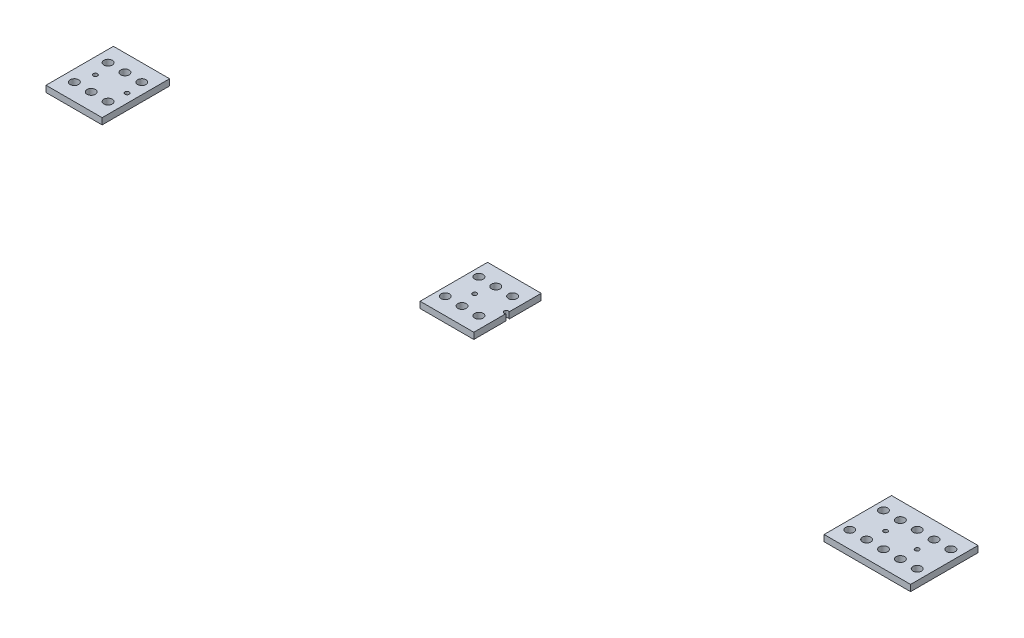
SolidWorks part; units mm, degrees
ref_plane "前基準面" through (0, 0, 0) normal (0, 0, 1) x (1, 0, 0)
ref_plane "上基準面" through (0, 0, 0) normal (0, 1, 0) x (1, 0, 0)
ref_plane "右基準面" through (0, 0, 0) normal (1, 0, 0) x (0, 0, -1)
sketch "草圖1" plane through (0, 0, 0) normal (0, 1, 0) x (1, 0, 0)
  line L1 (437.0323, 21.7005) -> (-14.2241, 21.7005)
  line L2 (437.0323, 21.7005) -> (437.0323, -10.2995)
  line L3 (437.0323, -10.2995) -> (-14.2241, -10.2995)
  line L4 (-14.2241, 21.7005) -> (-14.2241, -10.2995)
  line L5 (211.4041, -10.2995) -> (211.4041, 21.7005) construction
  line L6 (437.0323, 5.7005) -> (-14.2241, 5.7005) construction
  circle A0 centre (-8.7706, 13.7005) radius 2
  circle A1 centre (-8.7706, -2.2995) radius 2
  circle A2 centre (-0.7706, 13.7005) radius 2
  circle A3 centre (-0.7706, -2.2995) radius 2
  circle A4 centre (7.2294, 13.7005) radius 2
  circle A5 centre (7.2294, -2.2995) radius 2
  circle A6 centre (15.2294, 13.7005) radius 2
  circle A7 centre (15.2294, -2.2995) radius 2
  circle A8 centre (23.2294, 13.7005) radius 2
  circle A9 centre (23.2294, -2.2995) radius 2
  circle A10 centre (31.2294, 13.7005) radius 2
  circle A11 centre (31.2294, -2.2995) radius 2
  circle A12 centre (39.2294, 13.7005) radius 2
  circle A13 centre (39.2294, -2.2995) radius 2
  circle A14 centre (47.2294, 13.7005) radius 2
  circle A15 centre (47.2294, -2.2995) radius 2
  circle A16 centre (55.2294, 13.7005) radius 2
  circle A17 centre (55.2294, -2.2995) radius 2
  circle A18 centre (63.2294, 13.7005) radius 2
  circle A19 centre (63.2294, -2.2995) radius 2
  circle A20 centre (71.2294, 13.7005) radius 2
  circle A21 centre (71.2294, -2.2995) radius 2
  circle A22 centre (79.2294, 13.7005) radius 2
  circle A23 centre (79.2294, -2.2995) radius 2
  circle A24 centre (87.2294, 13.7005) radius 2
  circle A25 centre (87.2294, -2.2995) radius 2
  circle A26 centre (95.2294, 13.7005) radius 2
  circle A27 centre (95.2294, -2.2995) radius 2
  circle A28 centre (103.2294, 13.7005) radius 2
  circle A29 centre (103.2294, -2.2995) radius 2
  circle A30 centre (111.2294, 13.7005) radius 2
  circle A31 centre (111.2294, -2.2995) radius 2
  circle A32 centre (119.2294, 13.7005) radius 2
  circle A33 centre (119.2294, -2.2995) radius 2
  circle A34 centre (127.2294, 13.7005) radius 2
  circle A35 centre (127.2294, -2.2995) radius 2
  circle A36 centre (135.2294, 13.7005) radius 2
  circle A37 centre (135.2294, -2.2995) radius 2
  circle A38 centre (143.2294, 13.7005) radius 2
  circle A39 centre (143.2294, -2.2995) radius 2
  circle A40 centre (151.2294, 13.7005) radius 2
  circle A41 centre (151.2294, -2.2995) radius 2
  circle A42 centre (159.2294, 13.7005) radius 2
  circle A43 centre (159.2294, -2.2995) radius 2
  circle A44 centre (167.2294, 13.7005) radius 2
  circle A45 centre (167.2294, -2.2995) radius 2
  circle A46 centre (175.2294, 13.7005) radius 2
  circle A47 centre (175.2294, -2.2995) radius 2
  circle A48 centre (183.2294, 13.7005) radius 2
  circle A49 centre (183.2294, -2.2995) radius 2
  circle A50 centre (191.2294, 13.7005) radius 2
  circle A51 centre (191.2294, -2.2995) radius 2
  circle A52 centre (199.2294, 13.7005) radius 2
  circle A53 centre (199.2294, -2.2995) radius 2
  circle A54 centre (207.2294, 13.7005) radius 2
  circle A55 centre (207.2294, -2.2995) radius 2
  circle A56 centre (215.2294, 13.7005) radius 2
  circle A57 centre (215.2294, -2.2995) radius 2
  circle A58 centre (223.2294, 13.7005) radius 2
  circle A59 centre (223.2294, -2.2995) radius 2
  circle A60 centre (231.2294, 13.7005) radius 2
  circle A61 centre (231.2294, -2.2995) radius 2
  circle A62 centre (239.2294, 13.7005) radius 2
  circle A63 centre (239.2294, -2.2995) radius 2
  circle A64 centre (247.2294, 13.7005) radius 2
  circle A65 centre (247.2294, -2.2995) radius 2
  circle A66 centre (255.2294, 13.7005) radius 2
  circle A67 centre (255.2294, -2.2995) radius 2
  circle A68 centre (263.2294, 13.7005) radius 2
  circle A69 centre (263.2294, -2.2995) radius 2
  circle A70 centre (271.2294, 13.7005) radius 2
  circle A71 centre (271.2294, -2.2995) radius 2
  circle A72 centre (279.2294, 13.7005) radius 2
  circle A73 centre (279.2294, -2.2995) radius 2
  circle A74 centre (287.2294, 13.7005) radius 2
  circle A75 centre (287.2294, -2.2995) radius 2
  circle A76 centre (295.2294, 13.7005) radius 2
  circle A77 centre (295.2294, -2.2995) radius 2
  circle A78 centre (303.2294, 13.7005) radius 2
  circle A79 centre (303.2294, -2.2995) radius 2
  circle A80 centre (311.2294, 13.7005) radius 2
  circle A81 centre (311.2294, -2.2995) radius 2
  circle A82 centre (319.2294, 13.7005) radius 2
  circle A83 centre (319.2294, -2.2995) radius 2
  circle A84 centre (327.2294, 13.7005) radius 2
  circle A85 centre (327.2294, -2.2995) radius 2
  circle A86 centre (335.2294, 13.7005) radius 2
  circle A87 centre (335.2294, -2.2995) radius 2
  circle A88 centre (343.2294, 13.7005) radius 2
  circle A89 centre (343.2294, -2.2995) radius 2
  circle A90 centre (351.2294, 13.7005) radius 2
  circle A91 centre (351.2294, -2.2995) radius 2
  circle A92 centre (359.2294, 13.7005) radius 2
  circle A93 centre (359.2294, -2.2995) radius 2
  circle A94 centre (367.2294, 13.7005) radius 2
  circle A95 centre (367.2294, -2.2995) radius 2
  circle A96 centre (375.2294, 13.7005) radius 2
  circle A97 centre (375.2294, -2.2995) radius 2
  circle A98 centre (383.2294, 13.7005) radius 2
  circle A99 centre (383.2294, -2.2995) radius 2
  circle A100 centre (391.2294, 13.7005) radius 2
  circle A101 centre (391.2294, -2.2995) radius 2
  circle A102 centre (399.2294, 13.7005) radius 2
  circle A103 centre (399.2294, -2.2995) radius 2
  circle A104 centre (407.2294, 13.7005) radius 2
  circle A105 centre (407.2294, -2.2995) radius 2
  circle A106 centre (415.2294, 13.7005) radius 2
  circle A107 centre (415.2294, -2.2995) radius 2
  circle A108 centre (423.2294, 13.7005) radius 2
  circle A109 centre (423.2294, -2.2995) radius 2
  circle A110 centre (431.2294, 13.7005) radius 2
  circle A111 centre (431.2294, -2.2995) radius 2
  circle A112 centre (-6.7706, 5.7005) radius 1
  circle A113 centre (8.2294, 5.7005) radius 1
  circle A114 centre (23.2294, 5.7005) radius 1
  circle A115 centre (38.2294, 5.7005) radius 1
  circle A116 centre (53.2294, 5.7005) radius 1
  circle A117 centre (68.2294, 5.7005) radius 1
  circle A118 centre (83.2294, 5.7005) radius 1
  circle A119 centre (98.2294, 5.7005) radius 1
  circle A120 centre (113.2294, 5.7005) radius 1
  circle A121 centre (128.2294, 5.7005) radius 1
  circle A122 centre (143.2294, 5.7005) radius 1
  circle A123 centre (158.2294, 5.7005) radius 1
  circle A124 centre (173.2294, 5.7005) radius 1
  circle A125 centre (188.2294, 5.7005) radius 1
  circle A126 centre (203.2294, 5.7005) radius 1
  circle A127 centre (218.2294, 5.7005) radius 1
  circle A128 centre (233.2294, 5.7005) radius 1
  circle A129 centre (248.2294, 5.7005) radius 1
  circle A130 centre (263.2294, 5.7005) radius 1
  circle A131 centre (278.2294, 5.7005) radius 1
  circle A132 centre (293.2294, 5.7005) radius 1
  circle A133 centre (308.2294, 5.7005) radius 1
  circle A134 centre (323.2294, 5.7005) radius 1
  circle A135 centre (338.2294, 5.7005) radius 1
  circle A136 centre (353.2294, 5.7005) radius 1
  circle A137 centre (368.2294, 5.7005) radius 1
  circle A138 centre (383.2294, 5.7005) radius 1
  point P1018 (211.4041, 5.7005)
  dimension "D1" = 4
  dimension "D2" = 4
  dimension "D5" = 2
  dimension "D3" = 16
  dimension "D6" = 8
  dimension "D8" = 32
  dimension "D9" = 16
  dimension "D4" = 56
  dimension "D7" = 27
extrude "填料-伸長1" add sketch "草圖1" along normal blind 3
sketch "草圖2" plane through (0, 3, 0) normal (0, 1, 0) x (1, 0, 0)
  line L0 (437.0323, 21.7005) -> (-14.2241, 21.7005) construction
  line L1 (12.4203, 21.7005) -> (163.3256, 21.7005)
  line L2 (12.4203, 21.7005) -> (12.4203, -10.2995)
  line L3 (12.4203, -10.2995) -> (163.3256, -10.2995)
  line L4 (163.3256, 21.7005) -> (163.3256, -10.2995)
  line L5 (87.8729, -10.2995) -> (87.8729, 21.7005) construction
  line L6 (12.4203, 5.7005) -> (163.3256, 5.7005) construction
  line L7 (-14.2241, -10.2995) -> (437.0323, -10.2995) construction
  line L9 (188.8026, 21.7005) -> (355.05, 21.7005)
  line L10 (188.8026, 21.7005) -> (188.8026, -10.2995)
  line L11 (188.8026, -10.2995) -> (355.05, -10.2995)
  line L12 (355.05, 21.7005) -> (355.05, -10.2995)
  line L13 (271.9263, -10.2995) -> (271.9263, 21.7005) construction
  line L14 (188.8026, 5.7005) -> (355.05, 5.7005) construction
  line L15 (396.0865, 21.7005) -> (437.0323, 21.7005)
  line L16 (396.0865, 21.7005) -> (396.0865, -10.2995)
  line L17 (396.0865, -10.2995) -> (437.0323, -10.2995)
  line L18 (437.0323, 21.7005) -> (437.0323, -10.2995)
  line L19 (416.5594, -10.2995) -> (416.5594, 21.7005) construction
  line L20 (396.0865, 5.7005) -> (437.0323, 5.7005) construction
  point P288 (416.5594, 5.7005)
  point P420 (271.9263, 5.7005)
  point P1332 (87.8729, 5.7005)
extrude "除料-伸長1" cut sketch "草圖2" against normal blind 3
